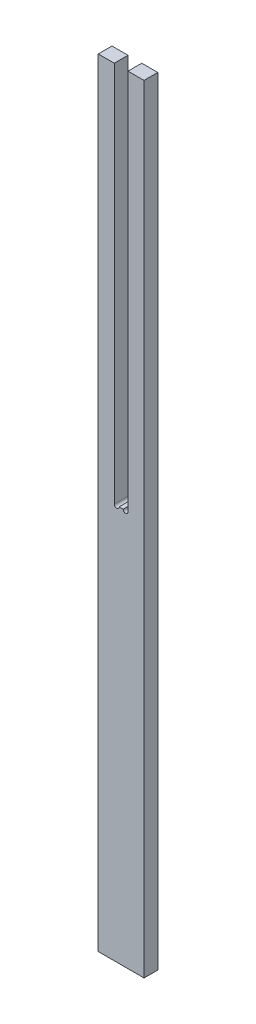
SolidWorks part; units mm, degrees
ref_plane "Piano frontale" through (0, 0, 0) normal (0, 0, 1) x (1, 0, 0)
ref_plane "Piano superiore" through (0, 0, 0) normal (0, 1, 0) x (1, 0, 0)
ref_plane "Piano destro" through (0, 0, 0) normal (1, 0, 0) x (0, 0, -1)
sketch "Schizzo1" plane through (0, 0, 0) normal (0, 0, 1) x (1, 0, 0)
  line L0 (-51.2222, 843) -> (-51.2222, 343)
  line L1 (-72.2222, 843) -> (-51.2222, 843)
  line L2 (-72.2222, 843) -> (-72.2222, -175)
  line L3 (-72.2222, -175) -> (-12.2222, -175)
  line L4 (-12.2222, 843) -> (-12.2222, -175)
  line L7 (-44.8722, 343) -> (-39.5722, 343)
  line L8 (-33.2222, 343) -> (-33.2222, 843)
  line L9 (-33.2222, 843) -> (-12.2222, 843)
  arc A0 (-33.2222, 343) -> (-39.5722, 343) centre (-36.3972, 343) cw
  arc A1 (-51.2222, 343) -> (-44.8722, 343) centre (-48.0472, 343) ccw
  point P0 (-42.766, 343)
  dimension "D5" = 3.175
  dimension "D6" = 3.175
  dimension "D1" = 60
  dimension "D2" = 1018
  dimension "D3" = 18
  dimension "D4" = 21
extrude "Estrusione-Estrusione1" add sketch "Schizzo1" along normal blind 18 contours L4 L3 L2 L1 L0 A1 L7 A0 L8 L9
